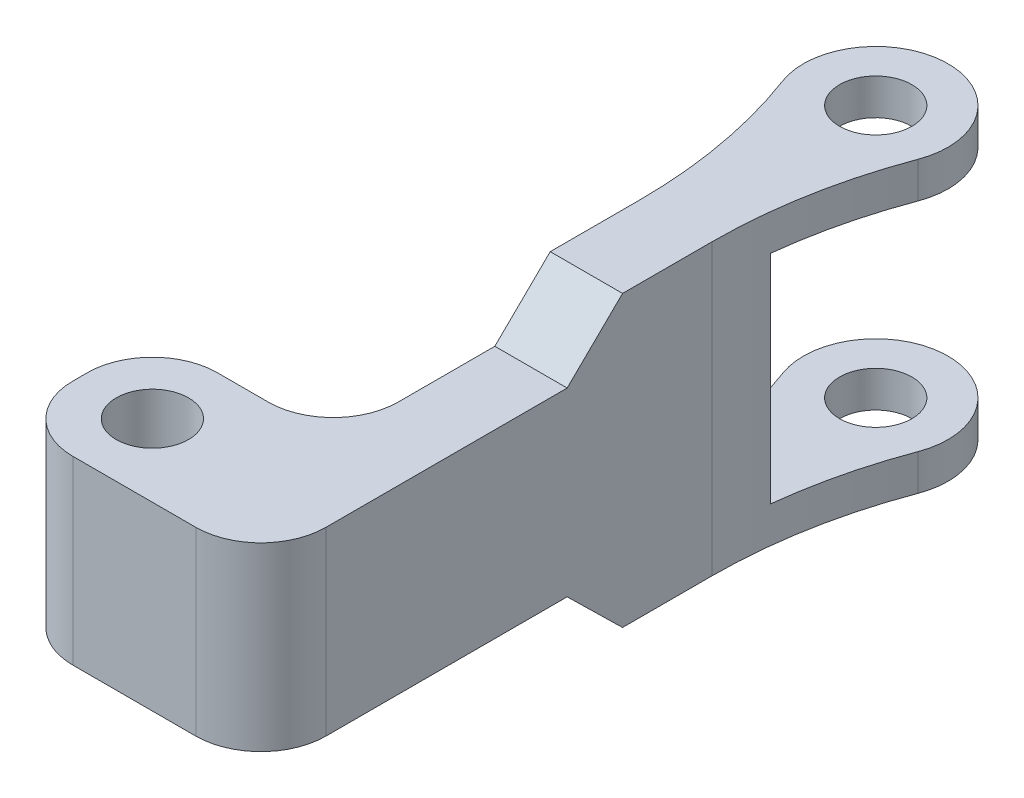
SolidWorks part; units mm, degrees
material "6061 Alloy"
ref_plane "Front Plane" through (0, 0, 0) normal (0, 0, 1) x (1, 0, 0)
ref_plane "Top Plane" through (0, 0, 0) normal (0, 1, 0) x (1, 0, 0)
ref_plane "Right Plane" through (0, 0, 0) normal (1, 0, 0) x (0, 0, -1)
sketch "Sketch1" plane through (0, 0, 0) normal (0, 1, 0) x (1, 0, 0)
  line L27 (7.5, 9.5) -> (7.5, 26.1707)
  line L28 (12.5, 15) -> (12.5, -0.5)
  line L29 (12.5, 15) -> (12.5, 26.1707)
  line L32 (-0.5, -5) -> (8, -5)
  line L33 (-5, -0.5) -> (-5, 0.5)
  line L34 (-0.5, 5) -> (3, 5)
  circle A0 centre (0, 0) radius 2.5
  circle A1 centre (0, 0) radius 5 construction
  circle A3 centre (10, 40) radius 2.5
  arc A8 (14.6835, 38.2495) -> (5.3165, 38.2495) centre (10, 40) ccw
  arc A9 (-0.5, -5) -> (-5, -0.5) centre (-0.5, -0.5) cw
  arc A10 (-0.5, 5) -> (-5, 0.5) centre (-0.5, 0.5) ccw
  arc A11 (12.5, -0.5) -> (8, -5) centre (8, -0.5) cw
  arc A12 (7.5, 9.5) -> (3, 5) centre (3, 9.5) cw
  arc A13 (12.5, 26.1707) -> (14.6835, 38.2495) centre (47, 26.1707) cw
  arc A14 (7.5, 26.1707) -> (5.3165, 38.2495) centre (-27, 26.1707) ccw
  dimension "D1" = 10
  dimension "D2" = 5
  dimension "D8" = 45
  dimension "D4" = 5
  dimension "D5" = 34.5
  dimension "D3" = 4.5
  dimension "D9" = 5
  dimension "D10" = 35
  dimension "D6" = 11.1707
  dimension "D7" = 8.5
extrude "Boss-Extrude1" add sketch "Sketch1" along normal blind 25
ref_plane "Plane1" through (14.6835, 25, -38.2495) normal (0, -1, 0) x (-1, 0, 0)
sketch "Sketch4" plane through (0, 0, 0) normal (1, 0, 0) x (0, 0, -1)
  line L0 (37.501, 12.6198) -> (37.501, 10.1198) construction
  line L2 (45.001, 20) -> (45.001, 5)
  line L3 (45.001, 5) -> (30.001, 5)
  line L4 (30.001, 5) -> (30.001, 20)
  line L6 (30.001, 20) -> (45.001, 20)
  line L7 (-5, 0) -> (45, 0) construction
  line L9 (-5, 6.25) -> (-5, 18.75) construction
  line L10 (45, 25) -> (45, 22.5)
  line L11 (45, 22.5) -> (20, 22.5)
  line L12 (-5, 18.75) -> (16.1707, 18.75)
  line L13 (16.1707, 18.75) -> (20, 22.5)
  line L14 (45, 25) -> (-5, 25)
  line L15 (-5, 25) -> (-5, 18.75)
  line L16 (45, 0) -> (-5, 0)
  line L17 (-5, 0) -> (-5, 6.25)
  line L18 (45, 0) -> (45, 2.5)
  line L19 (45, 2.5) -> (20, 2.5)
  line L20 (-5, 6.25) -> (16.1707, 6.25)
  line L21 (16.1707, 6.25) -> (20, 2.5)
  dimension "D5" = 6.25
  dimension "D7" = 50
  dimension "D1" = 2.5
  dimension "D2" = 15
  dimension "D3" = 15
  dimension "D4" = 5
  dimension "D6" = 12.5
  dimension "D8" = 50
extrude "Cut-Extrude2" cut sketch "Sketch4" along normal through all and the other way through all
